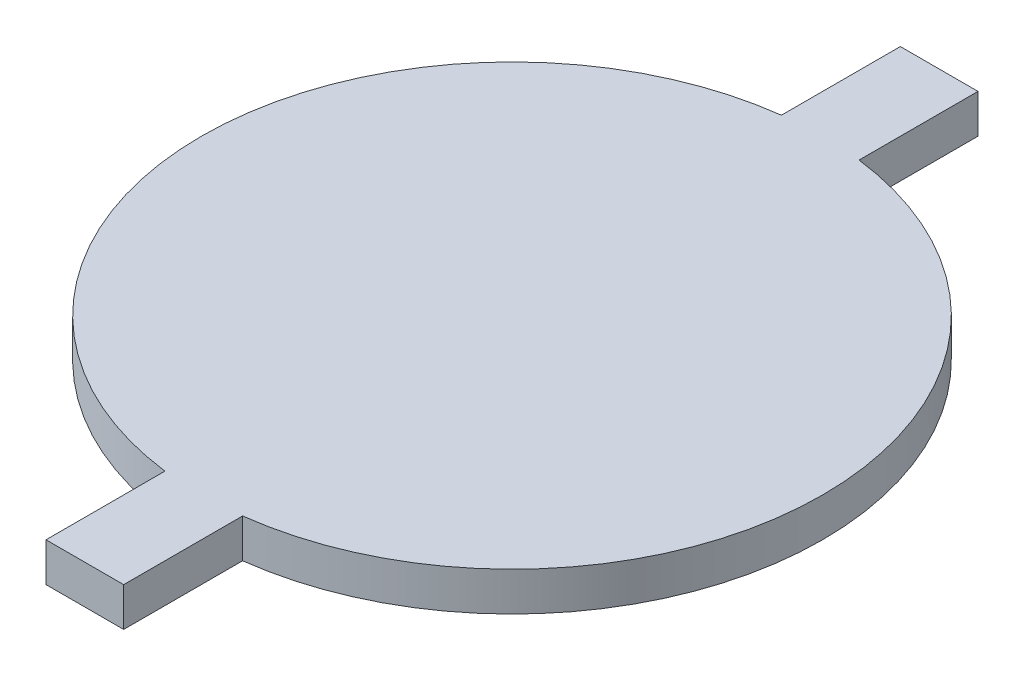
SolidWorks part; units mm, degrees
ref_plane "Front Plane" through (0, 0, 0) normal (0, 0, 1) x (1, 0, 0)
ref_plane "Top Plane" through (0, 0, 0) normal (0, 1, 0) x (1, 0, 0)
ref_plane "Right Plane" through (0, 0, 0) normal (1, 0, 0) x (0, 0, -1)
sketch "Sketch1" plane through (0, 0, 0) normal (0, 1, 0) x (1, 0, 0)
  line L1 (5, -55) -> (-5, -55)
  line L2 (5, -55) -> (5, 55)
  line L3 (5, 55) -> (-5, 55)
  line L4 (-5, -55) -> (-5, 55)
  line L5 (5, -55) -> (-5, 55) construction
  line L6 (5, 55) -> (-5, -55) construction
  circle A0 centre (0, 0) radius 40
  dimension "D1" = 80
  dimension "D2" = 10
  dimension "D3" = 110
extrude "Boss-Extrude1" add sketch "Sketch1" along normal blind 5 contours L4 A0 | A0 L2 L3 L4 | L2 A0 | L2 A0 L4 | A0 L4 L1 L2
sketch "Sketch2" plane through (0, 0, 0) normal (0, -1, 0) x (1, 0, 0)
  line L0 (0, -2.75) -> (0, 2.75) construction
  circle A0 centre (0, 50) radius 3
  circle A1 centre (0, 50) radius 4.5
  dimension "D1" = 6
  dimension "D3" = 9
  dimension "D2" = 50
